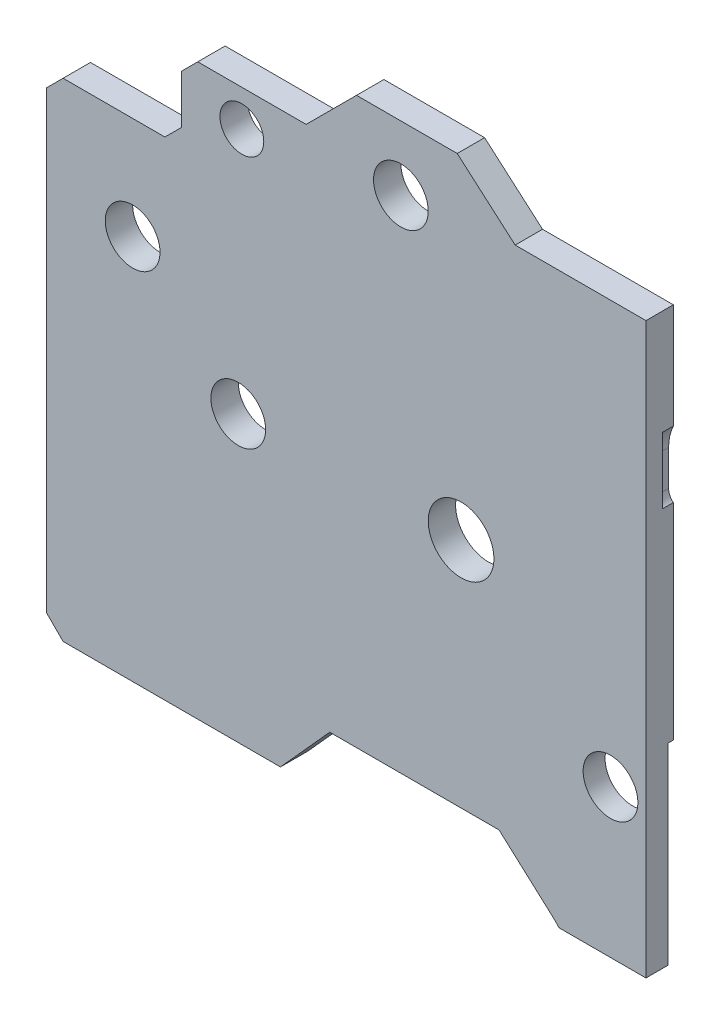
SolidWorks part; units mm, degrees
ref_plane "정면" through (0, 0, 0) normal (0, 0, 1) x (1, 0, 0)
ref_plane "윗면" through (0, 0, 0) normal (0, 1, 0) x (1, 0, 0)
ref_plane "우측면" through (0, 0, 0) normal (1, 0, 0) x (0, 0, -1)
sketch "스케치1" plane through (0, 0, 0) normal (0, 0, 1) x (1, 0, 0)
  line L0 (-7.6943, -28.1969) -> (-3.1923, -23.1969)
  line L1 (-0.7492, 28.4031) -> (8.4508, 28.4031)
  line L2 (-43.0492, 8.9031) -> (-43.0492, -28.1969)
  line L3 (-43.0492, -28.1969) -> (-7.6943, -28.1969)
  line L4 (40.6508, 12.1831) -> (40.6508, -28.1969)
  line L5 (-3.1923, -23.1969) -> (12.2677, -23.1969)
  line L6 (12.2677, -23.1969) -> (17.8208, -28.1969)
  line L7 (17.8208, -28.1969) -> (40.6508, -28.1969)
  line L8 (-28.1492, 23.8031) -> (-43.0492, 8.9031)
  line L9 (28.9925, 23.8031) -> (40.6508, 12.1831)
  line L10 (-0.7492, 28.4031) -> (-5.3492, 23.8031)
  line L11 (-5.3492, 23.8031) -> (-28.1492, 23.8031)
  line L12 (8.4508, 28.4031) -> (13.7425, 23.8031)
  line L13 (13.7425, 23.8031) -> (28.9925, 23.8031)
  line L14 (13.7425, 23.8031) -> (9.84, 23.8031) construction
  line L15 (27.6508, -14.6969) -> (27.6508, -28.1969)
  line L16 (27.6508, -28.1969) -> (17.8208, -28.1969)
  line L17 (17.2508, -27.6836) -> (17.2508, -14.6969)
  line L18 (-29.9492, -7.7002) -> (-29.9492, -28.1969)
  line L19 (-27.3492, -28.1969) -> (-37.7492, -28.1969)
  line L20 (-37.7492, -28.1969) -> (-37.7492, -3.1969)
  circle A0 centre (-21.1975, 7.0131) radius 2.5
  circle A1 centre (3.3025, 22.5131) radius 2.5
  circle A2 centre (8.8025, -1.9869) radius 3
  arc A3 (-29.9492, -7.7002) -> (-37.7492, -3.1969) centre (-32.5492, -3.1969) ccw
  circle A4 centre (-32.5492, -3.1969) radius 2.5
  circle A5 centre (22.4508, -14.6969) radius 5.2
  circle A6 centre (22.4508, -14.6969) radius 2.5
  point P0 (-1.1998, -0.6969)
  dimension "D1" = 5
  dimension "D2" = 5
  dimension "D3" = 6
  dimension "D9" = 5
  dimension "D10" = 10.4
  dimension "D11" = 5
  dimension "D12" = 10.4
  dimension "D13" = 10.5
  dimension "D4" = 24.5
  dimension "D5" = 24.5
  dimension "D6" = 30
  dimension "D7" = 15.5
  dimension "D8" = 9
  dimension "D14" = 25
  dimension "D15" = 18.2
  dimension "D16" = 13.5
  dimension "D17" = 5
  dimension "D18" = 52
  dimension "D19" = 4.6
  dimension "D20" = 9.2
  dimension "D21" = 41
  dimension "D22" = 15.25
  dimension "D23" = 83.7
  dimension "D24" = 37.1
  dimension "D25" = 135
  dimension "D26" = 40.38
  dimension "D27" = 22.8
  dimension "D28" = 135
  dimension "D29" = 15.46
  dimension "D30" = 132
  dimension "D31" = 22.83
  dimension "D32" = 10.44
  dimension "D33" = 5.89
extrude "보스-돌출1" add sketch "스케치1" along normal blind 2.5 contours L13 L12 L1 L10 L11 L8 L2 L3 L0 L5 L6 L7 L4 L9 A5 A3 A2 A1 A0
sketch "스케치3" plane through (0, 0, 2.5) normal (0, 0, 1) x (1, 0, 0)
  line L0 (27.6508, -14.6969) -> (27.6508, -28.1969)
  line L1 (17.2508, -14.6969) -> (17.2508, -27.6836)
  line L2 (17.2508, -27.6836) -> (17.764, -28.1969)
  line L3 (17.764, -28.1969) -> (27.6508, -28.1969)
  line L4 (-29.9492, -7.7002) -> (-29.9492, -28.1969)
  line L5 (-30.0492, -28.1969) -> (-37.7492, -28.1969)
  line L6 (-37.7492, -28.1969) -> (-37.7492, -3.1969)
  line L8 (-29.9492, -28.1969) -> (-30.0492, -28.1969)
  circle A0 centre (-32.5492, -3.1969) radius 5.2 construction
  arc A1 (-27.3492, -3.1969) -> (-37.7492, -3.1969) centre (-32.5492, -3.1969) ccw
  circle A2 centre (-32.5492, -3.1969) radius 2.5
  circle A3 centre (22.4508, -14.6969) radius 5.2 construction
  arc A4 (27.6508, -14.6969) -> (17.2508, -14.6969) centre (22.4508, -14.6969) ccw
  circle A5 centre (22.4508, -14.6969) radius 2.5
  arc A6 (-29.9492, -7.7002) -> (-37.7492, -3.1969) centre (-32.5492, -3.1969) ccw
  dimension "D1" = 5
  dimension "D2" = 5
  dimension "D3" = 135
extrude "보스-돌출3" add sketch "스케치3" against normal blind 2
sketch "스케치6" plane through (0, 0, 2.5) normal (0, 0, 1) x (1, 0, 0)
  line L0 (26.4064, 8.0587) -> (32.8952, 8.0587) construction
  line L1 (33.8952, 9.0587) -> (33.8952, 15.5475) construction
  line L2 (32.8952, 16.5475) -> (29.6508, 16.5475) construction
  line L3 (25.4064, 9.0587) -> (25.4064, 12.3031) construction
  line L4 (40.6508, 12.1831) -> (40.6508, -28.1969) construction
  line L5 (17.764, -28.1969) -> (40.6508, -28.1969) construction
  arc A0 (29.6508, 16.5475) -> (25.4064, 12.3031) centre (29.6508, 12.3031) ccw construction
  arc A1 (26.4064, 8.0587) -> (25.4064, 9.0587) centre (26.4064, 9.0587) cw construction
  arc A2 (32.8952, 8.0587) -> (33.8952, 9.0587) centre (32.8952, 9.0587) ccw construction
  arc A3 (33.8952, 15.5475) -> (32.8952, 16.5475) centre (32.8952, 15.5475) ccw construction
  dimension "D1" = 1
  dimension "D2" = 11
  dimension "D3" = 40.5
  dimension "D4" = 8.4888
sketch "스케치7" plane through (0, 0, 0) normal (0, 0, -1) x (-1, 0, 0)
  line L0 (-33.8952, 9.0587) -> (-33.8952, 15.5475) construction
  line L1 (-32.8952, 16.5475) -> (-29.6508, 16.5475) construction
  line L2 (-25.4064, 9.0587) -> (-25.4064, 12.3031) construction
  line L3 (-26.4064, 8.0587) -> (-32.8952, 8.0587) construction
  line L4 (-33.8952, 9.0587) -> (-33.8952, 15.5475)
  line L5 (-32.8952, 16.5475) -> (-29.6508, 16.5475)
  line L6 (-25.4064, 9.0587) -> (-25.4064, 12.3031)
  line L7 (-26.4064, 8.0587) -> (-32.8952, 8.0587)
  line L8 (-26.4064, 7.9087) -> (-32.8952, 7.9087)
  line L9 (-34.0452, 9.0587) -> (-34.0452, 15.5475)
  line L10 (-32.8952, 16.6975) -> (-29.6508, 16.6975)
  line L11 (-25.2564, 9.0587) -> (-25.2564, 12.3031)
  line L14 (-13.7425, 23.8031) -> (-28.9925, 23.8031)
  line L15 (-28.9925, 23.8031) -> (-40.6508, 12.1831)
  line L16 (-40.6508, 12.1831) -> (-40.6508, -28.1969)
  line L17 (-40.6508, -28.1969) -> (-27.6508, -28.1969)
  line L18 (-17.2508, -27.6836) -> (-12.2677, -23.1969)
  line L19 (-12.2677, -23.1969) -> (3.1923, -23.1969)
  line L20 (3.1923, -23.1969) -> (7.6943, -28.1969)
  line L21 (7.6943, -28.1969) -> (29.9492, -28.1969)
  line L22 (43.0492, -28.1969) -> (43.0492, 8.9031)
  line L23 (43.0492, 8.9031) -> (28.1492, 23.8031)
  line L24 (28.1492, 23.8031) -> (5.3492, 23.8031)
  line L25 (5.3492, 23.8031) -> (0.7492, 28.4031)
  line L26 (0.7492, 28.4031) -> (-8.4508, 28.4031)
  line L27 (-8.4508, 28.4031) -> (-13.7425, 23.8031)
  line L28 (-13.7425, 23.8031) -> (-28.9925, 23.8031)
  line L29 (-28.9925, 23.8031) -> (-40.6508, 12.1831)
  line L30 (-40.6508, 12.1831) -> (-40.6508, -28.1969)
  line L31 (-40.6508, -28.1969) -> (-27.6508, -28.1969)
  line L32 (-17.2508, -27.6836) -> (-12.2677, -23.1969)
  line L33 (-12.2677, -23.1969) -> (3.1923, -23.1969)
  line L34 (3.1923, -23.1969) -> (7.6943, -28.1969)
  line L35 (7.6943, -28.1969) -> (29.9492, -28.1969)
  line L36 (43.0492, -28.1969) -> (43.0492, 8.9031)
  line L37 (43.0492, 8.9031) -> (28.1492, 23.8031)
  line L38 (28.1492, 23.8031) -> (5.3492, 23.8031)
  line L39 (5.3492, 23.8031) -> (0.7492, 28.4031)
  line L40 (0.7492, 28.4031) -> (-8.4508, 28.4031)
  line L41 (-8.4508, 28.4031) -> (-13.7425, 23.8031)
  line L59 (29.9492, -28.1969) -> (29.9492, -7.7002)
  line L60 (29.9492, -28.1969) -> (29.9492, -7.7002)
  line L61 (-27.6508, -28.1969) -> (-27.6508, -14.6969)
  line L62 (-27.6508, -28.1969) -> (-27.6508, -14.6969)
  line L63 (-17.2508, -14.6969) -> (-17.2508, -27.6836)
  line L64 (-17.2508, -14.6969) -> (-17.2508, -27.6836)
  line L65 (37.7492, -3.1969) -> (37.7492, -28.1969)
  line L66 (37.7492, -3.1969) -> (37.7492, -28.1969)
  line L67 (37.7492, -28.1969) -> (43.0492, -28.1969)
  line L68 (37.7492, -28.1969) -> (43.0492, -28.1969)
  arc A0 (-32.8952, 16.5475) -> (-33.8952, 15.5475) centre (-32.8952, 15.5475) ccw construction
  arc A1 (-25.4064, 12.3031) -> (-29.6508, 16.5475) centre (-29.6508, 12.3031) ccw construction
  arc A2 (-26.4064, 8.0587) -> (-25.4064, 9.0587) centre (-26.4064, 9.0587) ccw construction
  arc A3 (-33.8952, 9.0587) -> (-32.8952, 8.0587) centre (-32.8952, 9.0587) ccw construction
  arc A4 (-32.8952, 16.5475) -> (-33.8952, 15.5475) centre (-32.8952, 15.5475) ccw
  arc A5 (-25.4064, 12.3031) -> (-29.6508, 16.5475) centre (-29.6508, 12.3031) ccw
  arc A6 (-26.4064, 8.0587) -> (-25.4064, 9.0587) centre (-26.4064, 9.0587) ccw
  arc A7 (-33.8952, 9.0587) -> (-32.8952, 8.0587) centre (-32.8952, 9.0587) ccw
  circle A8 centre (8.0492, -24.1969) radius 2.5
  circle A9 centre (6.1492, 20.8031) radius 2.5
  arc A10 (-34.0452, 9.0587) -> (-32.8952, 7.9087) centre (-32.8952, 9.0587) ccw
  arc A11 (-32.8952, 16.6975) -> (-34.0452, 15.5475) centre (-32.8952, 15.5475) ccw
  arc A12 (-25.2564, 12.3031) -> (-29.6508, 16.6975) centre (-29.6508, 12.3031) ccw
  arc A13 (-26.4064, 7.9087) -> (-25.2564, 9.0587) centre (-26.4064, 9.0587) ccw
  circle A14 centre (6.1492, 20.8031) radius 2.65
  circle A15 centre (8.0492, -24.1969) radius 2.65
  arc A18 (37.7492, -3.1969) -> (29.9492, -7.7002) centre (32.5492, -3.1969) ccw
  arc A19 (37.7492, -3.1969) -> (29.9492, -7.7002) centre (32.5492, -3.1969) ccw
  arc A20 (-17.2508, -14.6969) -> (-27.6508, -14.6969) centre (-22.4508, -14.6969) ccw
  arc A21 (-17.2508, -14.6969) -> (-27.6508, -14.6969) centre (-22.4508, -14.6969) ccw
  dimension "D2" = 5
  dimension "D5" = 5
  dimension "D3" = 4
  dimension "D4" = 35
  dimension "D6" = 3
  dimension "D7" = 22
  dimension "D1" = 0
  dimension "D8" = 0.15
extrude "컷-돌출1" cut sketch "스케치7" against normal blind 1 contours A8 | A9 | L8 A13 L11 A12 L10 A11 L9 A10 A7 L4 A4 L5 A5 L6 A6 L7 | A15 A8 | L38 A14 A9
chamfer "모따기1" distance 1 angle 45 2 edges at (-43.0492, -28.1969, 1.25) (40.6508, -28.1969, 1.25)
sketch "스케치10" plane through (0, 0, 1) normal (0, 0, -1) x (-1, 0, 0)
  line L0 (-33.7084, 16.3607) -> (-25.5932, 8.2456) construction
  arc A0 (-32.8952, 16.6975) -> (-34.0452, 15.5475) centre (-32.8952, 15.5475) ccw construction
  arc A1 (-26.4064, 7.9087) -> (-25.2564, 9.0587) centre (-26.4064, 9.0587) ccw construction
  circle A2 centre (-29.6508, 12.3031) radius 2.5
  dimension "D1" = 5
extrude "컷-돌출3" cut sketch "스케치10" against normal up to next
sketch "스케치11" plane through (0, 0, 2.5) normal (0, 0, 1) x (1, 0, 0)
  point P1 (29.6508, 12.3031)
  point P2 (22.4508, -14.6969)
  point P3 (-32.5492, -3.1969)
sketch "스케치12" plane through (0, 0, 0) normal (0, 0, -1) x (-1, 0, 0)
  line L0 (16.7492, 23.8031) -> (16.7492, 16.3531)
  line L1 (5.3492, 23.8031) -> (28.1492, 23.8031) construction
  line L2 (16.7492, 16.3531) -> (35.5992, 16.3531)
  line L3 (28.1492, 23.8031) -> (43.0492, 8.9031) construction
  line L4 (35.5992, 16.3531) -> (28.1492, 23.8031)
  line L5 (28.1492, 23.8031) -> (16.7492, 23.8031)
extrude "컷-돌출4" cut sketch "스케치12" against normal up to next
chamfer "모따기2" distance 1.5 angle 45 2 edges at (-16.7492, 23.8031, 1.25) (-16.7492, 16.3531, 1.25)
sketch "스케치13" plane through (0, 0, 0) normal (0, 0, -1) x (-1, 0, 0)
  line L2 (-34.6893, 18.1251) -> (-34.6893, -28.1969)
  line L3 (38.0492, 13.9031) -> (43.0492, 8.9031)
  line L4 (43.0492, 8.9031) -> (43.0492, -27.1969)
  line L5 (43.0492, -27.1969) -> (42.0492, -28.1969)
  line L6 (42.0492, -28.1969) -> (38.0492, -28.1969)
  line L7 (-40.6508, 12.1831) -> (-34.6893, 18.1251)
  line L8 (-28.9925, 23.8031) -> (-40.6508, 12.1831) construction
  line L17 (-40.6508, 12.1831) -> (-40.6508, -27.1969)
  line L18 (-40.6508, -27.1969) -> (-39.6508, -28.1969)
  line L19 (-39.6508, -28.1969) -> (-34.6893, -28.1969)
  line L20 (38.0492, 13.9031) -> (38.0492, -28.1969)
  dimension "D1" = 5.5
  dimension "D2" = 5.0385
extrude "컷-돌출5" cut sketch "스케치13" against normal up to next
chamfer "모따기3" distance 2 angle 45 2 edges at (-38.0492, -28.1969, 1.25) (34.6893, -28.1969, 1.25)
sketch "스케치14" plane through (0, 0, 0) normal (0, 0, -1) x (-1, 0, 0)
  line L0 (-34.6893, -4.0359) -> (37.7492, -4.0359) construction
  line L1 (-34.6893, -26.1969) -> (-34.6893, 18.1251) construction
  line L2 (37.7492, -26.4969) -> (37.7492, -3.1969) construction
sketch "스케치15" plane through (0, 0, 2.5) normal (0, 0, 1) x (1, 0, 0)
  line L0 (-18.2492, 16.3531) -> (-35.5992, 16.3531) construction
  line L1 (-29.0492, 16.3531) -> (-38.0492, 16.3531)
  line L2 (-29.0492, 16.3531) -> (-29.0492, -28.1969)
  line L3 (-29.0492, -28.1969) -> (-38.0492, -28.1969)
  line L4 (-38.0492, 16.3531) -> (-38.0492, -28.1969)
  line L5 (13.7425, 23.8031) -> (28.9925, 23.8031) construction
  line L6 (25.6893, 23.8031) -> (34.6893, 23.8031)
  line L7 (25.6893, 23.8031) -> (25.6893, -28.1969)
  line L8 (25.6893, -28.1969) -> (34.6893, -28.1969)
  line L9 (34.6893, 23.8031) -> (34.6893, -28.1969)
  line L10 (-36.0492, -28.1969) -> (-7.6943, -28.1969) construction
  line L11 (17.764, -28.1969) -> (32.6893, -28.1969) construction
  line L12 (-38.0492, 13.9031) -> (-38.0492, -26.1969) construction
  line L13 (34.6893, -26.1969) -> (34.6893, 18.1251) construction
  dimension "D1" = 9
  dimension "D2" = 9
extrude "컷-돌출6" cut sketch "스케치15" against normal up to next
sketch "스케치16" plane through (0, 0, 0) normal (0, 0, -1) x (-1, 0, 0)
  line L0 (16.7492, 22.3031) -> (16.7492, 17.8531) construction
  line L1 (29.0492, -28.1969) -> (7.6943, -28.1969) construction
  circle A0 centre (11.5492, -2.1969) radius 2.5
  dimension "D1" = 5
  dimension "D2" = 5.2
  dimension "D3" = 26
extrude "컷-돌출7" cut sketch "스케치16" against normal up to next
chamfer "모따기4" distance 1.5 angle 45 2 edges at (-29.0492, -28.1969, 1.25) (-29.0492, 16.3531, 1.25)
sketch "스케치17" plane through (0, 0, 0) normal (0, 0, -1) x (-1, 0, 0)
  line L0 (5.3492, 23.8031) -> (15.2492, 23.8031) construction
  line L1 (16.7492, 22.3031) -> (16.7492, 17.8531) construction
  circle A0 centre (11.2192, 20.5031) radius 2
  dimension "D1" = 4
  dimension "D2" = 3.3
  dimension "D3" = 5.53
extrude "컷-돌출8" cut sketch "스케치17" against normal blind 10
